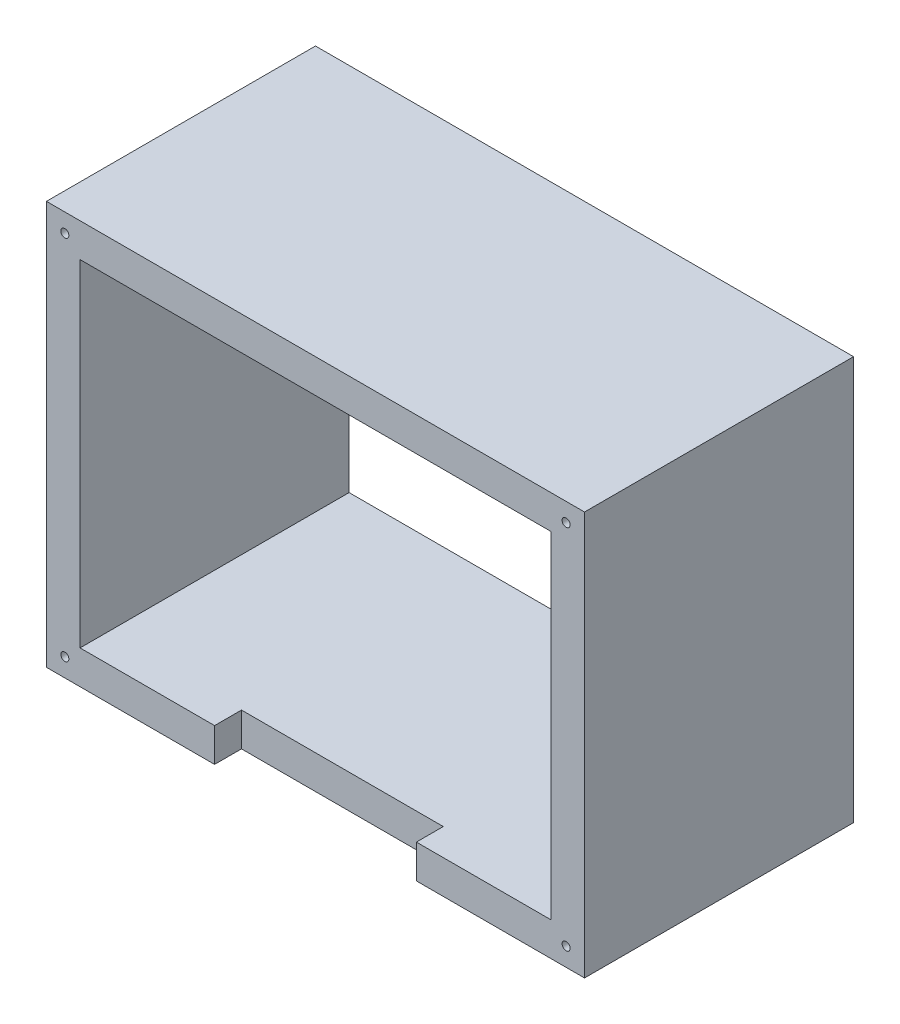
SolidWorks part; units mm, degrees
ref_plane "Front Plane" through (0, 0, 0) normal (0, 0, 1) x (1, 0, 0)
ref_plane "Top Plane" through (0, 0, 0) normal (0, 1, 0) x (1, 0, 0)
ref_plane "Right Plane" through (0, 0, 0) normal (1, 0, 0) x (0, 0, -1)
sketch "Sketch1" plane through (0, 0, 0) normal (0, 0, 1) x (1, 0, 0)
  line L1 (-88.8349, 57.3807) -> (111.1651, 57.3807)
  line L2 (-88.8349, 57.3807) -> (-88.8349, -92.6193)
  line L3 (-88.8349, -92.6193) -> (111.1651, -92.6193)
  line L4 (111.1651, 57.3807) -> (111.1651, -92.6193)
  dimension "D1" = 200
  dimension "D2" = 150
extrude "Boss-Extrude1" add sketch "Sketch1" along normal blind 100
sketch "Sketch2" plane through (0, 0, 0) normal (0, 0, -1) x (-1, 0, 0)
  line L0 (88.8349, -92.6193) -> (-111.1651, -92.6193) construction
  line L1 (-98.6651, 44.8807) -> (76.3349, 44.8807)
  line L2 (-98.6651, 44.8807) -> (-98.6651, -80.1193)
  line L3 (-98.6651, -80.1193) -> (76.3349, -80.1193)
  line L4 (76.3349, 44.8807) -> (76.3349, -80.1193)
  line L9 (-111.1651, -92.6193) -> (-111.1651, 57.3807) construction
  dimension "D1" = 125
  dimension "D2" = 12.5
  dimension "D3" = 175
  dimension "D4" = 12.5
extrude "Cut-Extrude1" cut sketch "Sketch2" against normal blind 100
sketch "Sketch3" plane through (0, -80.1193, 0) normal (0, 1, 0) x (1, 0, 0)
  line L0 (98.6651, -100) -> (-76.3349, -100) construction
  line L1 (48.6651, -90) -> (-26.3349, -90)
  line L2 (48.6651, -90) -> (48.6651, -100)
  line L3 (48.6651, -100) -> (-26.3349, -100)
  line L4 (-26.3349, -90) -> (-26.3349, -100)
  line L5 (98.6651, -100) -> (98.6651, 0) construction
  line L6 (-76.3349, -100) -> (-76.3349, 0) construction
  dimension "D1" = 50
  dimension "D2" = 50
  dimension "D3" = 10
extrude "Cut-Extrude2" cut sketch "Sketch3" against normal blind 15
sketch "Sketch4" plane through (0, 0, 100) normal (0, 0, 1) x (1, 0, 0)
  circle A0 centre (-81.9917, 50.5376) radius 1.5
  circle A1 centre (-81.9917, -85.7761) radius 1.5
  circle A2 centre (104.322, 50.5376) radius 1.5
  circle A3 centre (104.322, -85.7761) radius 1.5
extrude "Cut-Extrude3" cut sketch "Sketch4" against normal blind 20
